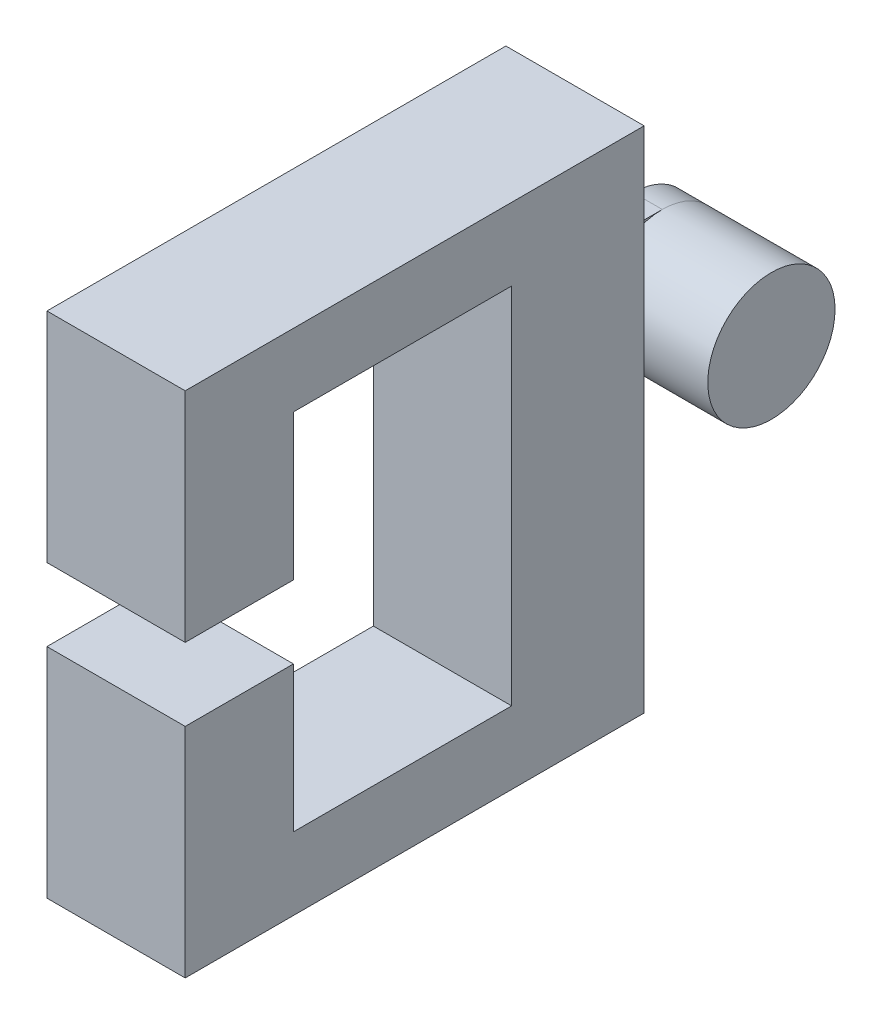
SolidWorks part; units mm, degrees
material "ASTM A36 Steel"
ref_plane "Front Plane" through (0, 0, 0) normal (1, 0, 0) x (0, 1, 0)
ref_plane "Top Plane" through (0, 0, 0) normal (0, 0, 1) x (0, 1, 0)
ref_plane "Right Plane" through (0, 0, 0) normal (0, 1, 0) x (-1, 0, 0)
sketch "Base Sketch" plane through (0, 0, 0) normal (1, 0, 0) x (0, 1, 0)
  line L1 (-44.3992, 23.1391) -> (44.3992, 23.1391)
  line L2 (-44.3992, 23.1391) -> (-44.3992, 0)
  line L3 (-44.3992, 0) -> (44.3992, 0)
  line L4 (44.3992, 23.1391) -> (44.3992, 0)
  line L5 (-44.3992, 23.1391) -> (44.3992, 0) construction
  line L6 (-44.3992, 0) -> (44.3992, 23.1391) construction
  line L7 (-11.1129, 0) -> (11.1129, 0)
  line L8 (-11.1129, 0) -> (-11.1129, -33.3385)
  line L9 (-11.1129, -33.3385) -> (11.1129, -33.3385)
  line L10 (11.1129, 0) -> (11.1129, -33.3385)
  line L11 (-11.1129, 0) -> (11.1129, -33.3385) construction
  line L12 (-11.1129, -33.3385) -> (11.1129, 0) construction
  line L13 (-44.3992, 61.2391) -> (-31.75, 61.2391)
  line L14 (-44.3992, 61.2391) -> (-44.3992, 23.1391)
  line L15 (-44.3992, 23.1391) -> (-31.75, 23.1391)
  line L16 (-31.75, 61.2391) -> (-31.75, 23.1391)
  line L17 (-44.3992, 61.2391) -> (-31.75, 23.1391) construction
  line L18 (-44.3992, 23.1391) -> (-31.75, 61.2391) construction
  line L19 (31.75, 61.2391) -> (44.3992, 61.2391)
  line L20 (31.75, 61.2391) -> (31.75, 23.1391)
  line L21 (31.75, 23.1391) -> (44.3992, 23.1391)
  line L22 (44.3992, 61.2391) -> (44.3992, 23.1391)
  line L23 (31.75, 61.2391) -> (44.3992, 23.1391) construction
  line L24 (31.75, 23.1391) -> (44.3992, 61.2391) construction
  line L25 (-44.3992, 80.1385) -> (-6.35, 80.1385)
  line L26 (-44.3992, 80.1385) -> (-44.3992, 61.2391)
  line L27 (-44.3992, 61.2391) -> (-6.35, 61.2391)
  line L28 (-6.35, 80.1385) -> (-6.35, 61.2391)
  line L29 (-44.3992, 80.1385) -> (-6.35, 61.2391) construction
  line L30 (-44.3992, 61.2391) -> (-6.35, 80.1385) construction
  line L31 (6.35, 80.1385) -> (44.3992, 80.1385)
  line L32 (6.35, 80.1385) -> (6.35, 61.2391)
  line L33 (6.35, 61.2391) -> (44.3992, 61.2391)
  line L34 (44.3992, 80.1385) -> (44.3992, 61.2391)
  line L35 (6.35, 80.1385) -> (44.3992, 61.2391) construction
  line L36 (6.35, 61.2391) -> (44.3992, 80.1385) construction
  circle A0 centre (0, -22.2256) radius 11.1129
  point P0 (0, 11.5696)
  point P5 (0, -16.6693)
  point P13 (-25.3746, 70.6888)
  point P15 (38.0746, 42.1891)
  point P16 (-38.0746, 42.1891)
  point P28 (0, 11.5626)
  point P29 (25.3746, 70.6888)
  dimension "D5" = 22.2258
  dimension "D6" = 12.7
  dimension "D1" = 23.1391
  dimension "D2" = 88.7984
  dimension "D3" = 22.2258
  dimension "D4" = 33.3385
  dimension "D7" = 38.1
  dimension "D8" = 25.4
  dimension "D9" = 18.8994
  dimension "D10" = 25.4
  dimension "D11" = 38.1
extrude "Feature A" add sketch "Base Sketch" along normal mid plane 19.05 contours A0
sketch "Feature B Sketch" plane through (-9.525, 0, 0) normal (-1, 0, 0) x (0, -1, 0)
  line L0 (11.1129, -33.3385) -> (-11.1129, -33.3385) construction
  line L1 (11.1129, 0) -> (11.1129, -33.3385) construction
  line L2 (-11.1129, 0) -> (-11.1129, -33.3385) construction
  line L3 (11.1129, -33.3385) -> (-11.1129, -33.3385)
  line L4 (11.1129, 0) -> (11.1129, -33.3385)
  line L5 (-11.1129, 0) -> (-11.1129, -33.3385)
  line L6 (-11.1129, 0) -> (11.1129, 0)
extrude "Feature B" add sketch "Feature B Sketch" along normal blind 5.0914 contours L5 L3 L4 L6
fillet "Fillet1" radius 11.1128 2 edges at (-9.525, 7.858, -30.0836) (-12.0707, 11.1129, -33.3385)
fillet "Fillet2" radius 11.1128 3 edges at (-12.0707, -11.1129, -33.3385) (-9.525, -7.858, -30.0836) (-9.525, -5.5564, -33.3385)
sketch "Feature C Sketch" plane through (9.525, 0, 0) normal (1, 0, 0) x (0, 1, 0)
  line L0 (44.3992, 23.1391) -> (44.3992, 0) construction
  line L1 (-44.3992, 0) -> (44.3992, 0) construction
  line L2 (-44.3992, 23.1391) -> (-44.3992, 0) construction
  line L3 (-44.3992, 23.1391) -> (44.3992, 23.1391) construction
  line L4 (44.3992, 23.1391) -> (44.3992, 0)
  line L5 (-44.3992, 0) -> (44.3992, 0)
  line L6 (-44.3992, 23.1391) -> (-44.3992, 0)
  line L7 (-44.3992, 23.1391) -> (44.3992, 23.1391)
  point P4 (44.3535, 0)
extrude "Feature C" add sketch "Feature C Sketch" against normal blind 24.1414
sketch "Feature D Sketch" plane through (9.525, 0, 0) normal (1, 0, 0) x (0, 1, 0)
  line L0 (44.3992, 61.2391) -> (44.3992, 23.1391) construction
  line L1 (31.75, 61.2391) -> (44.3992, 61.2391) construction
  line L2 (31.75, 61.2391) -> (31.75, 23.1391) construction
  line L3 (-44.3992, 23.1391) -> (44.3992, 23.1391) construction
  line L4 (-44.3992, 61.2391) -> (-31.75, 61.2391) construction
  line L5 (-44.3992, 61.2391) -> (-44.3992, 23.1391) construction
  line L6 (-31.75, 61.2391) -> (-31.75, 23.1391) construction
  line L7 (44.3992, 61.2391) -> (44.3992, 23.1391)
  line L8 (31.75, 61.2391) -> (44.3992, 61.2391)
  line L9 (31.75, 61.2391) -> (31.75, 23.1391)
  line L10 (-44.3992, 23.1391) -> (-31.75, 23.1391)
  line L11 (-44.3992, 61.2391) -> (-31.75, 61.2391)
  line L12 (-44.3992, 61.2391) -> (-44.3992, 23.1391)
  line L13 (-31.75, 61.2391) -> (-31.75, 23.1391)
  line L14 (31.75, 23.1391) -> (44.3992, 23.1391)
  line L16 (-44.3992, 23.1391) -> (44.3992, 23.1391)
  line M1 (44.3992, 23.1391) -> (-44.3992, 23.1391)
extrude "Feature D" add sketch "Feature D Sketch" against normal blind 24.1414 contours L8 L9 L7 M1 | L13 L11 L12 M1
sketch "Feature E Sketch" plane through (9.525, 0, 0) normal (1, 0, 0) x (0, 1, 0)
  line L0 (44.3992, 80.1385) -> (44.3992, 61.2391) construction
  line L1 (6.35, 80.1385) -> (44.3992, 80.1385) construction
  line L2 (6.35, 80.1385) -> (6.35, 61.2391) construction
  line L3 (6.35, 61.2391) -> (44.3992, 61.2391) construction
  line L4 (-44.3992, 80.1385) -> (-44.3992, 61.2391) construction
  line L5 (-44.3992, 80.1385) -> (-6.35, 80.1385) construction
  line L6 (-6.35, 80.1385) -> (-6.35, 61.2391) construction
  line L7 (-44.3992, 61.2391) -> (-6.35, 61.2391) construction
  line L8 (44.3992, 80.1385) -> (44.3992, 61.2391)
  line L9 (6.35, 80.1385) -> (44.3992, 80.1385)
  line L10 (6.35, 80.1385) -> (6.35, 61.2391)
  line L11 (6.35, 61.2391) -> (44.3992, 61.2391)
  line L12 (-44.3992, 80.1385) -> (-44.3992, 61.2391)
  line L13 (-44.3992, 80.1385) -> (-6.35, 80.1385)
  line L14 (-6.35, 80.1385) -> (-6.35, 61.2391)
  line L15 (-44.3992, 61.2391) -> (-6.35, 61.2391)
extrude "Feature E" add sketch "Feature E Sketch" against normal blind 24.1414
equation "\"F_load\"= 795'lbf"
equation "\"SF\"= 4"
equation "\"Yield Strength\"= 36259.43'psi"
equation "\"E\"= 29007550'psi"
equation "\"max deflection\"= 0.005in'in"
equation "\"a\"= 0.498in'RC7 Fit"
equation "\"b\"= 0.9992in'RC3 Fit"
equation "\"c\"= 1.499in'RC4 Fit"
equation "\"L_A\"= 0.750in"
equation "\"r_A\"= ( ( 4 * \"SF\" * \"F_load\" * \"L_A\" ) / ( pi * ( \"Yield Strength\" ) ) ) ^ ( 1 / 3 )'in"
equation "\"D_A\"= 2 * \"r_A\"'in"
equation "\"w_B\"= \"D_A\"'in"
equation "\"h_B\"= 1.5 * \"D_A\"'in"
equation "\"W_A\"= 2 * \"F_load\"'psi"
equation "\"F_B\"= \"W_A\"'psi"
equation "\"F_C\"= \"F_B\"'psi"
equation "\"F_D\"= \"F_C\" / 2'psi"
equation "\"F_E\"= \"F_D\"'psi"
equation "\"t_B\"= ( \"SF\" * \"F_B\" ) / ( \"w_B\" * \"Yield Strength\" )'in"
equation "\"L_C\" = \"w_D\" + \"Gap_a\" + 2 * \"Gap_b\"'in"
equation "\"Overall_L_C\"= 2 * \"w_D\" + \"Gap_a\" + 2 * \"Gap_b\"'in"
equation "\"w_C\"= \"L_A\" + \"t_B\"'in"
equation "\"t_C\"= ( ( 3 * \"F_C\" * \"L_C\" * \"SF\" ) / ( 2 * \"w_C\" * \"Yield Strength\" ) ) ^ ( 1 / 2 )'in"
equation "\"Overall_L_d\"= \"w_C\"'in"
equation "\"L_D\" = \"Gap_c\"'in"
equation "\"w_D_stress\"= ( \"SF\" * \"F_D\" ) / ( \"Overall_L_d\" * \"Yield Strength\" )"
equation "\"w_D\"= IIF ( \"w_D_stress\" > \"a\" , \"w_D_stress\" , \"a\" )'in"
equation "\"L_E\" = \"Gap_b\"'in"
equation "\"Overall_L_E\"= \"w_C\"'in"
equation "\"h_E\"= ( ( 6 * \"F_E\" * \"L_E\" * \"SF\" ) / ( \"Overall_L_E\" * \"Yield Strength\" ) ) ^ ( 1 / 2 )'in"
equation "\"Gap_a\"= 0.5000in"
equation "\"Gap_b\"= 1.0000in"
equation "\"Gap_c\"= 1.5000in"
